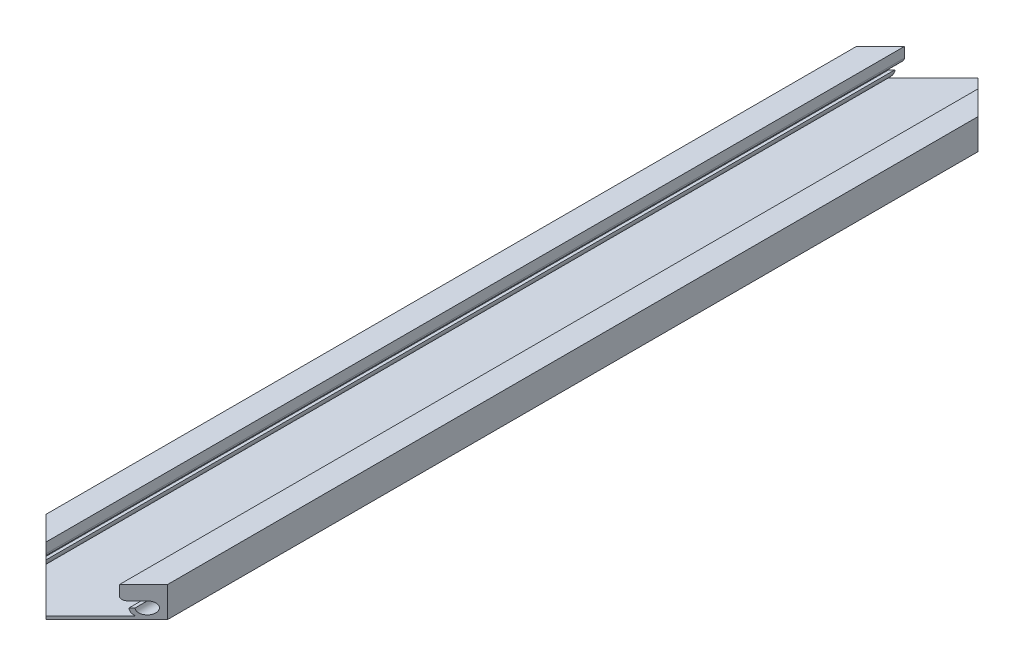
SolidWorks part; units mm, degrees
ref_plane "정면" through (0, 0, 0) normal (0, 0, 1) x (1, 0, 0)
ref_plane "윗면" through (0, 0, 0) normal (0, 1, 0) x (1, 0, 0)
ref_plane "우측면" through (0, 0, 0) normal (1, 0, 0) x (0, 0, -1)
sketch "스케치1" plane through (0, 0, 0) normal (0, 0, 1) x (1, 0, 0)
  line L1 (-30, 7.5) -> (30, 7.5)
  line L2 (-30, 7.5) -> (-30, -7.5)
  line L3 (-30, -7.5) -> (30, -7.5)
  line L4 (30, 7.5) -> (30, -7.5)
  line L5 (-30, 7.5) -> (30, -7.5) construction
  line L6 (-30, -7.5) -> (30, 7.5) construction
  point P0 (0, 0)
  dimension "D1" = 60
  dimension "D2" = 15
extrude "보스-돌출1" add sketch "스케치1" along normal blind 460
sketch "스케치2" plane through (0, 0, 0) normal (0, 0, -1) x (-1, 0, 0)
  line L0 (30, -7.5) -> (-30, -7.5) construction
  line L2 (-30, -7.5) -> (-30, 7.5) construction
  line L3 (30, 7.5) -> (30, -7.5) construction
  circle A0 centre (-25, -2.5) radius 3
  circle A1 centre (25, -2.5) radius 3
  dimension "D1" = 6
  dimension "D3" = 5
  dimension "D4" = 6
  dimension "D6" = 5
  dimension "D2" = 5
  dimension "D5" = 5
extrude "컷-돌출1" cut sketch "스케치2" against normal through all
sketch "스케치3" plane through (0, 0, 0) normal (0, 0, -1) x (-1, 0, 0)
  line L0 (-22.1716, -6) -> (22.1716, -6)
  line L1 (-20.5, -2.5) -> (-25, -2.5)
  line L2 (-25, -2.5) -> (-25, 0.5)
  line L3 (-25, 0.5) -> (25, 0.5)
  line L4 (25, 0.5) -> (25, -2.5)
  line L5 (25, -2.5) -> (20.5, -2.5)
  line L6 (30, -7.5) -> (-30, -7.5) construction
  arc A0 (22.1716, -6) -> (20.5, -2.5) centre (25, -2.5) cw
  arc A1 (-22.1716, -6) -> (-20.5, -2.5) centre (-25, -2.5) ccw
  circle A2 centre (-25, -2.5) radius 3 construction
  circle A3 centre (25, -2.5) radius 3 construction
  dimension "D2" = 1.5
  dimension "D1" = 1.5
  dimension "1.5" = 1.5
extrude "컷-돌출2" cut sketch "스케치3" against normal through all
sketch "스케치4" plane through (0, 0, 0) normal (0, 0, -1) x (-1, 0, 0)
  line L0 (-18.1431, 0.5) -> (18.1569, 0.5)
  line L1 (25, 0.5) -> (-25, 0.5) construction
  line L2 (-18.1431, 0.5) -> (-18.1431, 7.5)
  line L3 (-30, 7.5) -> (30, 7.5) construction
  line L4 (-18.1431, 7.5) -> (18.1569, 7.5)
  line L5 (18.1569, 7.5) -> (18.1569, 0.5)
  point P5 (0, 0)
  dimension "D1" = 36.3
extrude "컷-돌출3" cut sketch "스케치4" against normal through all
fillet "필렛1" radius 2 2 edges at (-18.1569, 0.5, 230) (18.1431, 0.5, 230)
sketch "스케치5" plane through (0, -7.5, 0) normal (0, -1, 0) x (1, 0, 0)
  line L0 (-30, 460) -> (-30, 430)
  line L1 (-30, 460) -> (-30, 0) construction
  line L2 (-30, 430) -> (0, 460)
  line L3 (-30, 460) -> (30, 460) construction
  line L4 (30, 460) -> (-30, 460)
  line L5 (0, 442.8165) -> (0, -66.3343) construction
  line L6 (-30, 230) -> (30, 230) construction
  line L7 (30, 460) -> (30, 0) construction
  line L8 (30, 430) -> (0, 460)
  line L9 (30, 460) -> (30, 430)
  line L10 (30, 0) -> (30, 30)
  line L11 (30, 30) -> (0, 0)
  line L12 (30, 0) -> (-30, 0)
  line L13 (-30, 30) -> (0, 0)
  line L14 (-30, 0) -> (-30, 30)
  line M8 (-30, 0) -> (30, 0)
  line M9 (30, 0) -> (30, 460)
  line M10 (30, 460) -> (-30, 460)
  line M11 (-30, 460) -> (-30, 0)
  dimension "D1" = 45
extrude "컷-돌출4" cut sketch "스케치5" against normal through all contours L8 M9 M10 | L2 M11 M10 | L13 M11 M8 | L11 M9 M8
